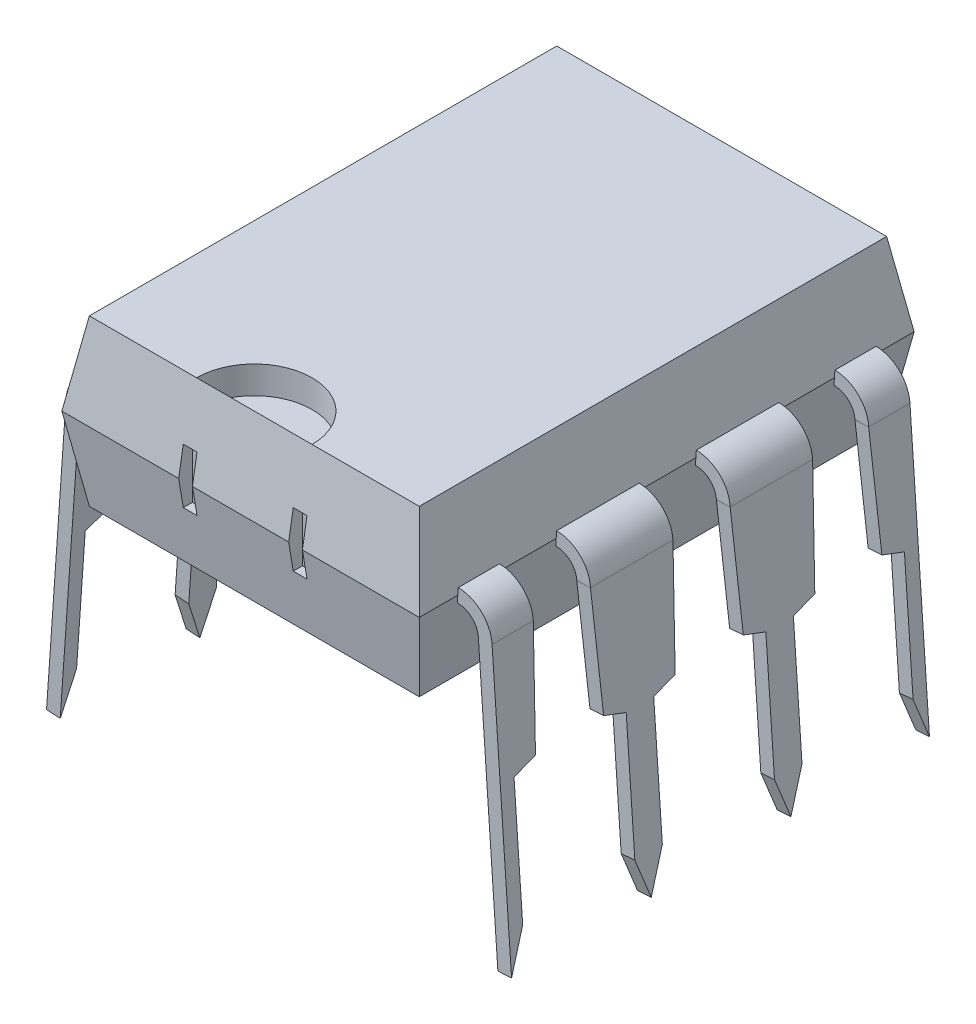
SolidWorks part; units mm, degrees
ref_plane "Front Plane" through (0, 0, 0) normal (0, 0, 1) x (1, 0, 0)
ref_plane "Top Plane" through (0, 0, 0) normal (0, 1, 0) x (1, 0, 0)
ref_plane "Right Plane" through (0, 0, 0) normal (1, 0, 0) x (0, 0, -1)
sketch "Sketch1" plane through (0, 0, 0) normal (0, 1, 0) x (1, 0, 0)
  line L0 (0, 4.25) -> (0, -4.25) construction
  line L1 (-3, 4.25) -> (3, 4.25)
  line L2 (-3, 4.25) -> (-3, -4.25)
  line L3 (-3, -4.25) -> (3, -4.25)
  line L4 (3, 4.25) -> (3, -4.25)
  line L5 (-3, 0) -> (3, 0) construction
  dimension "D1" = 6
  dimension "D2" = 8.5
ref_plane "Plane1" through (0, -1.5, 0) normal (0, 1, 0) x (1, 0, 0)
sketch "Sketch2" plane through (0, -1.5, 0) normal (0, 1, 0) x (1, 0, 0)
  line L1 (3.25, -4.5) -> (-3.25, -4.5)
  line L2 (3.25, -4.5) -> (3.25, 4.5)
  line L3 (3.25, 4.5) -> (-3.25, 4.5)
  line L4 (-3.25, -4.5) -> (-3.25, 4.5)
  line L5 (3.25, -4.5) -> (-3.25, 4.5) construction
  line L6 (3.25, 4.5) -> (-3.25, -4.5) construction
  point P0 (0, 0)
  dimension "D1" = 9
  dimension "D2" = 6.5
loft "Loft1" add profiles "Sketch1", "Sketch2"
mirror "Mirror1" of "Loft1"
sketch "Sketch7" plane through (0, 0, 0) normal (0, 1, 0) x (1, 0, 0)
  line L0 (0, 0) -> (0, -4.25) construction
  line L1 (-3, -4.25) -> (3, -4.25) construction
  line L3 (3.25, -4.5) -> (3.25, 4.5) construction
  line L4 (1.625, 0) -> (1.625, -4.5) construction
  line L7 (0, 0) -> (3.25, 0) construction
  line L9 (-3.25, -4.5) -> (3.25, -4.5) construction
  line L10 (-1.05, -4.25) -> (1.05, -4.25)
  circle A0 centre (1.625, -2.25) radius 1
  arc A1 (-1.05, -4.25) -> (1.05, -4.25) centre (0, -4.25) cw
  dimension "D1" = 2
  dimension "D3" = 1.05
  dimension "D2" = 2
extrude "Cut-Extrude3" cut sketch "Sketch7" against normal blind 0.5
ref_plane "Plane2" through (3.25, 0, 0) normal (1, 0, 0) x (0, 0, -1)
ref_plane "Plane3" through (0, 0, 4.5) normal (0, 0, 1) x (1, 0, 0)
ref_plane "Plane7" through (0, 0, -4.5) normal (0, 0, 1) x (1, 0, 0)
sketch "Sketch3" plane through (0, 0, 4.5) normal (0, 0, 1) x (1, 0, 0)
  line L0 (0, 0) -> (0, -3) construction
  line L1 (-3, -3) -> (3, -3) construction
  line L2 (-3, 0) -> (0, 0) construction
  line L3 (-3, 0) -> (-1.05, 0) construction
  line L4 (-1, 0) -> (-1, -3) construction
  line L5 (1, 0) -> (1, -3) construction
  line L6 (-3.25, -1.5) -> (3.25, -1.5) construction
  line L7 (-0.875, -2) -> (-1.125, -2)
  line L8 (-0.875, -2) -> (-0.875, -1)
  line L9 (-0.875, -1) -> (-1.125, -1)
  line L10 (-1.125, -2) -> (-1.125, -1)
  line L11 (-0.875, -2) -> (-1.125, -1) construction
  line L12 (-0.875, -1) -> (-1.125, -2) construction
  line L13 (0.875, -1) -> (1.125, -2) construction
  line L14 (0.875, -2) -> (1.125, -1) construction
  line L15 (1.125, -2) -> (1.125, -1)
  line L16 (0.875, -1) -> (1.125, -1)
  line L17 (0.875, -2) -> (0.875, -1)
  line L18 (0.875, -2) -> (1.125, -2)
  point P16 (-1, -1.5)
  point P25 (1, -1.5)
  dimension "D1" = 2
  dimension "D2" = 0.25
  dimension "D3" = 1
extrude "Cut-Extrude1" cut sketch "Sketch3" against normal blind 0.25
ref_plane "Plane4" through (0, 0, 3.8) normal (0, 0, 1) x (1, 0, 0)
sketch "Sketch4" plane through (0, 0, 3.8) normal (0, 0, 1) x (1, 0, 0)
  line L0 (3.25, -8.0133) -> (3.25, 8.0133) construction
  line L1 (1.125, -1.5) -> (3.25, -1.5) construction
  line L2 (3.75, -2) -> (3.75, -4.5908) construction
  line L3 (3.7488, -1.9651) -> (4.1045, -7.0527)
  line L4 (1.125, -1.5) -> (3.25, -1.5) construction
  arc A0 (3.7488, -1.9651) -> (3.25, -1.5) centre (3.25, -2) ccw
  dimension "D1" = 1
  dimension "D2" = 4
  dimension "D3" = 5.1
ref_plane "Plane5" through (0, -7.0527, 0) normal (0, 1, 0) x (1, 0, 0)
sketch "Sketch5" plane through (0, -7.0527, 0) normal (0, 1, 0) x (1, 0, 0)
  line L0 (3.7488, -3.8) -> (4.1045, -3.8) construction
  line L1 (3.9795, -4.55) -> (4.2295, -4.55)
  line L2 (3.9795, -4.55) -> (3.9795, -3.05)
  line L3 (3.9795, -3.05) -> (4.2295, -3.05)
  line L4 (4.2295, -4.55) -> (4.2295, -3.05)
  line L5 (3.9795, -4.55) -> (4.2295, -3.05) construction
  line L6 (3.9795, -3.05) -> (4.2295, -4.55) construction
  point P0 (4.1045, -3.8)
  dimension "D1" = 0.25
  dimension "D2" = 1.5
sweep "Sweep1" add profiles "Sketch5" path "Sketch4"
sketch "Sketch6" plane through (3.7182, 0.26, 0) normal (0.9976, 0.0698, 0) x (0, 0, -1)
  line L1 (-3.55, -4.3761) -> (-3.15, -4.2306)
  line L2 (-4.05, -6.6306) -> (-4.05, -4.3761)
  line L3 (-4.05, -4.3761) -> (-3.55, -4.3761)
  line L4 (-3.55, -6.6306) -> (-3.55, -4.3761)
  line L5 (-3.8, -2.2306) -> (-3.8, -7.3174) construction
  line L6 (-4.55, -2.2306) -> (-3.05, -2.2306) construction
  line L7 (-3.8, -7.3174) -> (-4.05, -6.6306)
  line L8 (-3.8, -7.3174) -> (-3.55, -6.6306)
  line L9 (-4.05, -4.3761) -> (-4.45, -4.2306)
  line L10 (-4.55, -7.3306) -> (-4.55, -2.2306) construction
  line L11 (-4.55, -3.8306) -> (-4.55, -7.3306)
  line L12 (-4.55, -7.3306) -> (-3.05, -7.3306)
  line L13 (-3.05, -7.3306) -> (-3.05, -3.8306)
  line L14 (-4.55, -2.2306) -> (-4.45, -4.2306)
  line L15 (-3.05, -2.2306) -> (-3.15, -4.2306)
  point P10 (-3.8, -4.3761)
  line M7 (-3.05, -7.3306) -> (-3.05, -2.2306)
  line M9 (-4.55, -2.2306) -> (-4.55, -7.3306)
  line M10 (-4.55, -7.3306) -> (-3.05, -7.3306)
  dimension "D1" = 0.5
  dimension "D2" = 0.7
  dimension "D3" = 20
  dimension "D4" = 20
  dimension "D5" = 3.5
  dimension "D6" = 1.3
  dimension "D7" = 2
extrude "Cut-Extrude2" cut sketch "Sketch6" against normal up to surface (0.2494 mm away) contours L2 L9 L1 L4 L8 L7 M9 M10 M7
pattern_linear "LPattern1" count 3 spacing 2.54 along (0, 0, -1) of bodies 106
ref_plane "Plane6" through (4.7158, 0.3298, 0) normal (0.9976, 0.0698, 0) x (0, 0, -1)
sketch "Sketch8" plane through (4.7158, 0.3298, 0) normal (0.9976, 0.0698, 0) x (0, 0, -1)
  line L1 (-3.8, -7.3174) -> (-4.6131, -7.3174)
  line L2 (-3.8, -7.3174) -> (-3.8, -1.5993)
  line L3 (-3.8, -1.5993) -> (-4.6131, -1.5993)
  line L4 (-4.6131, -7.3174) -> (-4.6131, -1.5993)
  line L5 (-4.55, -1.5993) -> (-3.05, -1.5993) construction
  line L6 (0, 0) -> (0, -8.2101) construction
  dimension "D1" = 0.8131
extrude "Cut-Extrude5" cut sketch "Sketch8" against normal up to surface (1.5724 mm away) contours L4 L1 L2 L3
mirror "Mirror4" about plane through (0, 0, 0) normal (0, 0, 1) of bodies 125
mirror "Mirror5" about plane through (0, 0, 0) normal (1, 0, 0) of bodies 122 123 127 125
sketch "Sketch9" plane through (0, 0, -4.5) normal (0, 0, 1) x (1, 0, 0)
  line L0 (0, 0) -> (0, -3) construction
  line L1 (-0.1282, -1.026) -> (0.1218, -2.026) construction
  line L2 (-0.1282, -2.026) -> (0.1218, -1.026) construction
  line L3 (0.1218, -2.026) -> (0.1218, -1.026)
  line L4 (-0.1282, -1.026) -> (0.1218, -1.026)
  line L5 (-0.1282, -2.026) -> (-0.1282, -1.026)
  line L6 (-0.1282, -2.026) -> (0.1218, -2.026)
  line L7 (3, -3) -> (-3, -3) construction
  line L8 (3.25, -1.5) -> (-3.25, -1.5) construction
  point P6 (0, -1.5)
  dimension "D1" = 1
  dimension "D2" = 0.25
extrude "Cut-Extrude6" cut sketch "Sketch9" along normal blind 0.25
